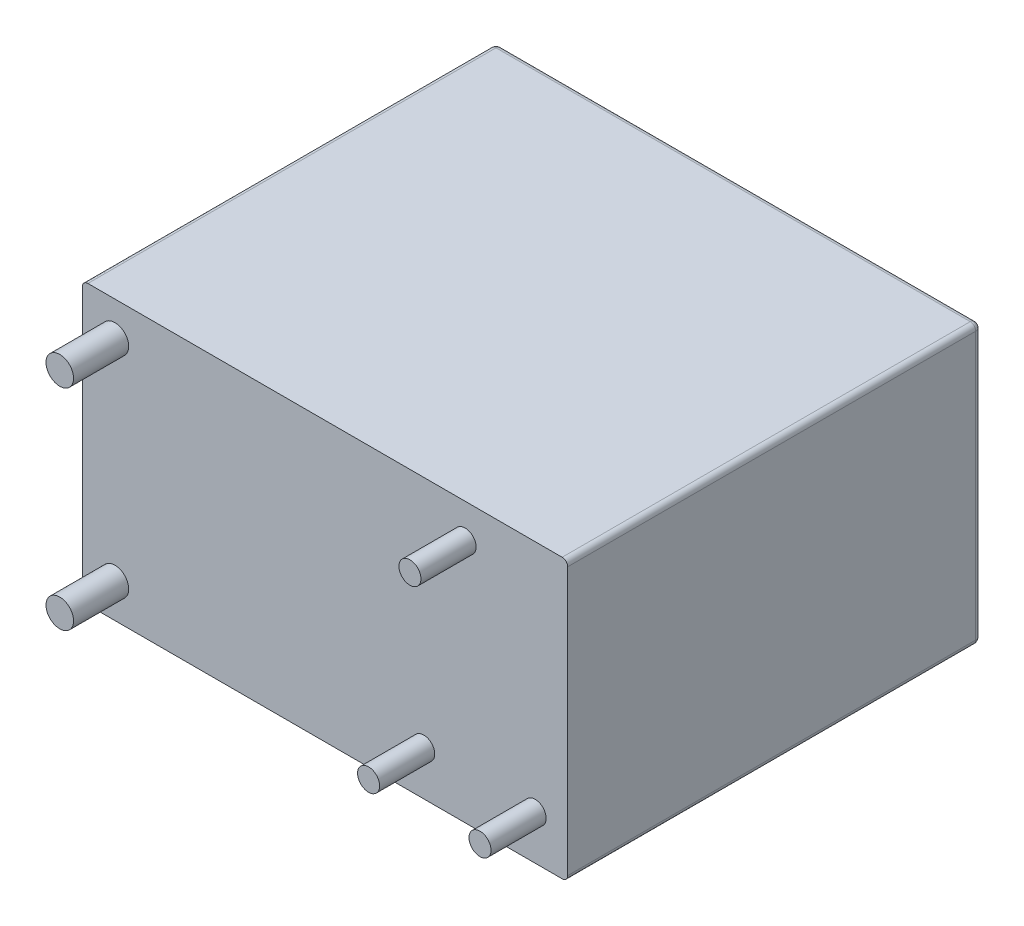
SolidWorks part; units mm, degrees
ref_plane "前视基准面" through (0, 0, 0) normal (0, 0, 1) x (1, 0, 0)
ref_plane "上视基准面" through (0, 0, 0) normal (0, 1, 0) x (1, 0, 0)
ref_plane "右视基准面" through (0, 0, 0) normal (1, 0, 0) x (0, 0, -1)
sketch "草图1" plane through (0, 0, 0) normal (0, 0, 1) x (1, 0, 0)
  line L1 (0, 0) -> (17.6, 0)
  line L2 (0, 0) -> (0, 10.1)
  line L3 (0, 10.1) -> (17.6, 10.1)
  line L4 (17.6, 0) -> (17.6, 10.1)
  dimension "D1" = 10.1
  dimension "D2" = 17.6
extrude "凸台-拉伸1" add sketch "草图1" against normal blind 15
sketch "草图2" plane through (0, 0, 0) normal (0, 0, 1) x (1, 0, 0)
  line L0 (0, 5.05) -> (17.6, 5.05) construction
  line L1 (0, 10.1) -> (0, 0) construction
  line L2 (17.6, 0) -> (17.6, 10.1) construction
  line L3 (8.8, 10.1) -> (8.8, 0) construction
  line L4 (17.6, 10.1) -> (0, 10.1) construction
  line L5 (0, 0) -> (17.6, 0) construction
  circle A0 centre (1.18, 8.86) radius 0.5
  circle A1 centre (13.88, 8.86) radius 0.4
  circle A2 centre (12.38, 1.607) radius 0.4
  circle A3 centre (16.42, 1.607) radius 0.4
  circle A4 centre (1.18, 1.24) radius 0.5
  dimension "D1" = 1
  dimension "D2" = 7.62
  dimension "D3" = 12.7
  dimension "D4" = 1.5
  dimension "D5" = 2.54
  dimension "D6" = 0.8
  dimension "D7" = 0.8
  dimension "D8" = 0.8
  dimension "D9" = 1.18
extrude "凸台-拉伸2" add sketch "草图2" along normal blind 2
fillet "圆角1" radius 0.2 8 edges at (17.6, 0, -7.5) (0, 0, -7.5) (8.8, 0, -15) (17.6, 5.05, -15) (0, 5.05, -15) (0, 10.1, -7.5) (17.6, 10.1, -7.5) (8.8, 10.1, -15)
sketch "草图3" plane through (0, 0, -15) normal (0, 0, -1) x (-1, 0, 0)
  circle A0 centre (-1.9393, 1.327) radius 0.5
  dimension "D1" = 1
extrude "切除-拉伸1" cut sketch "草图3" against normal blind 0.5
